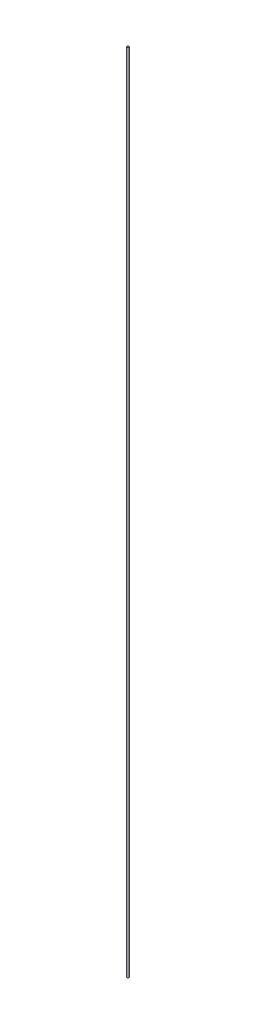
SolidWorks part; units mm, degrees
material "Cladding"
ref_plane "Front Plane" through (0, 0, 0) normal (0, 0, 1) x (1, 0, 0)
ref_plane "Top Plane" through (0, 0, 0) normal (0, 1, 0) x (1, 0, 0)
ref_plane "Right Plane" through (0, 0, 0) normal (1, 0, 0) x (0, 0, -1)
sketch "Sketch1" plane through (0, 0, 0) normal (0, 1, 0) x (1, 0, 0)
  circle A0 centre (0, 0) radius 4.88
  circle A1 centre (0, 0) radius 5.59
  dimension "D1" = 11.18
  dimension "D2" = 0.71
extrude "Boss-Extrude1" add sketch "Sketch1" along normal mid plane 4178.7
equation "\"EstCost\"=0.30*\"SW-Mass\""
